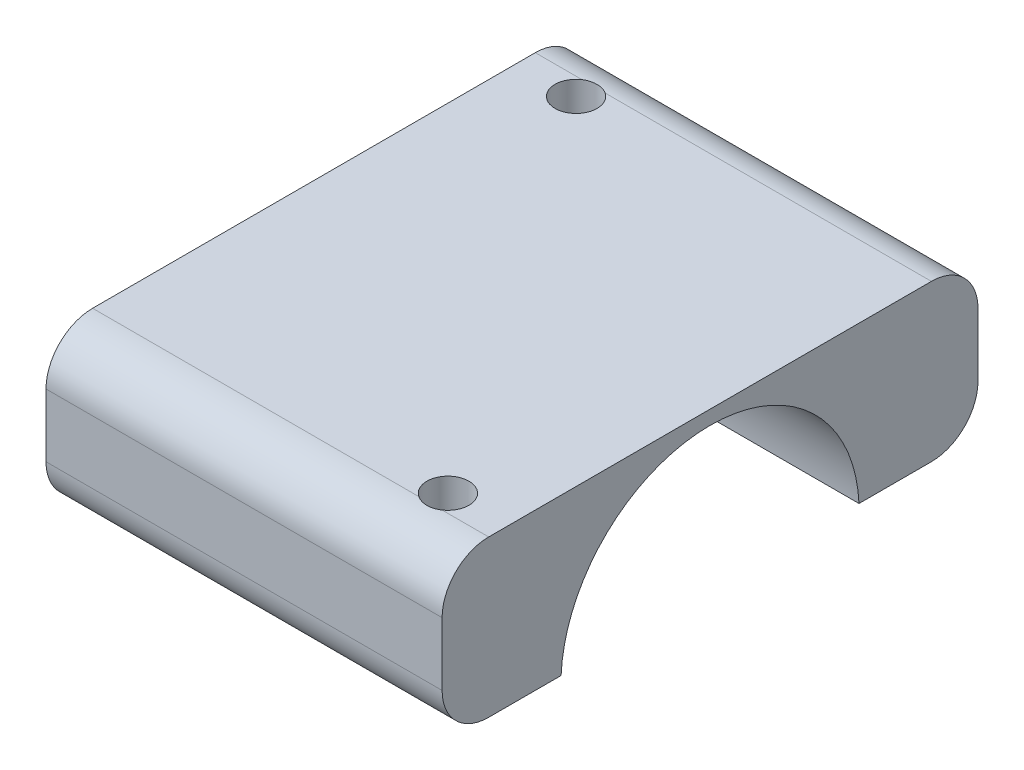
SolidWorks part; units mm, degrees
ref_plane "Front Plane" through (0, 0, 0) normal (0, 0, 1) x (1, 0, 0)
ref_plane "Top Plane" through (0, 0, 0) normal (0, 1, 0) x (1, 0, 0)
ref_plane "Right Plane" through (0, 0, 0) normal (1, 0, 0) x (0, 0, -1)
sketch "Sketch1" plane through (0, 0, 0) normal (1, 0, 0) x (0, 0, -1)
  line L0 (-19, 0.6) -> (19, 0.6)
  line L1 (23, 4.6) -> (23, 10.009)
  line L2 (19, 14.009) -> (-19, 14.009)
  line L3 (-23, 10.009) -> (-23, 4.6)
  arc A0 (19, 0.6) -> (23, 4.6) centre (19, 4.6) ccw
  arc A1 (23, 10.009) -> (19, 14.009) centre (19, 10.009) ccw
  arc A2 (-19, 14.009) -> (-23, 10.009) centre (-19, 10.009) ccw
  arc A3 (-23, 4.6) -> (-19, 0.6) centre (-19, 4.6) ccw
extrude "Boss-Extrude1" add sketch "Sketch1" along normal mid plane 34
sketch "Sketch2" plane through (0, 0, 0) normal (1, 0, 0) x (0, 0, -1)
  circle A0 centre (0, 0) radius 12.8
extrude "Cut-Extrude1" cut sketch "Sketch2" against normal through all and the other way through all
ref_plane "Plane1" through (0, 0.6, 0) normal (0, 1, 0) x (1, 0, 0)
sketch "Sketch3" plane through (0, 0.6, 0) normal (0, 1, 0) x (1, 0, 0)
  circle A0 centre (12, -17.5) radius 1.8
  circle A1 centre (-12, 17.5) radius 1.8
extrude "Cut-Extrude2" cut sketch "Sketch3" along normal blind 14.009
